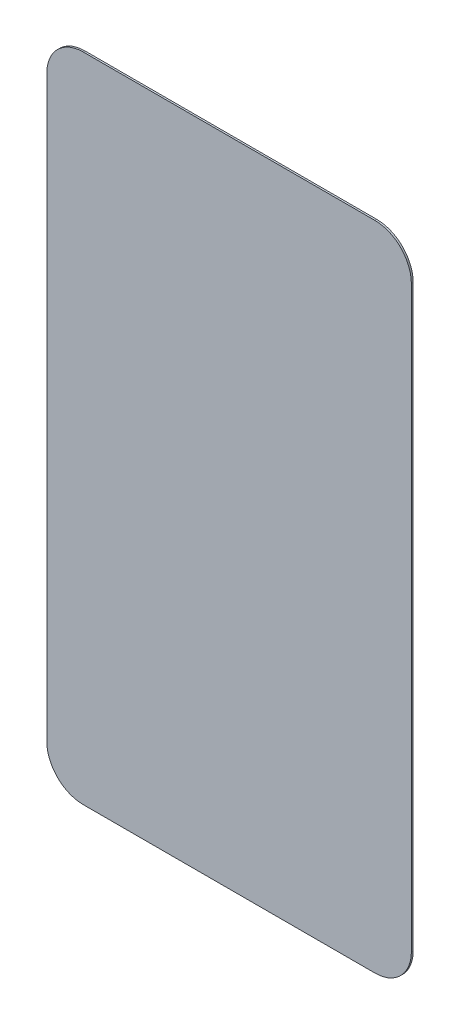
SolidWorks part; units mm, degrees
material "AISI 316 Нержавеющая сталь, лист (SS)"
ref_plane "Спереди" through (0, 0, 0) normal (0, 0, 1) x (1, 0, 0)
ref_plane "Сверху" through (0, 0, 0) normal (0, 1, 0) x (1, 0, 0)
ref_plane "Справа" through (0, 0, 0) normal (1, 0, 0) x (0, 0, -1)
sketch "Эскиз1" plane through (0, 0, 0) normal (0, 0, 1) x (1, 0, 0)
  line L0 (7.5315, 91.3436) -> (7.5315, 113.0789) construction
  line L1 (-32.4685, 91.3436) -> (47.5315, 91.3436)
  line L2 (-42.4685, 81.3436) -> (-42.4685, -77.4714)
  line L3 (-32.4685, -87.4714) -> (47.5315, -87.4714)
  line L4 (57.5315, 81.3436) -> (57.5315, -77.4714)
  arc A0 (-32.4685, 91.3436) -> (-42.4685, 81.3436) centre (-32.4685, 81.3436) ccw
  arc A1 (57.5315, 81.3436) -> (47.5315, 91.3436) centre (47.5315, 81.3436) ccw
  arc A2 (47.5315, -87.4714) -> (57.5315, -77.4714) centre (47.5315, -77.4714) ccw
  arc A3 (-42.4685, -77.4714) -> (-32.4685, -87.4714) centre (-32.4685, -77.4714) ccw
  dimension "D1" = 10
  dimension "D2" = 50
  dimension "D3" = 50
extrude "Вытянуть1" add sketch "Эскиз1" along normal blind 0.5
